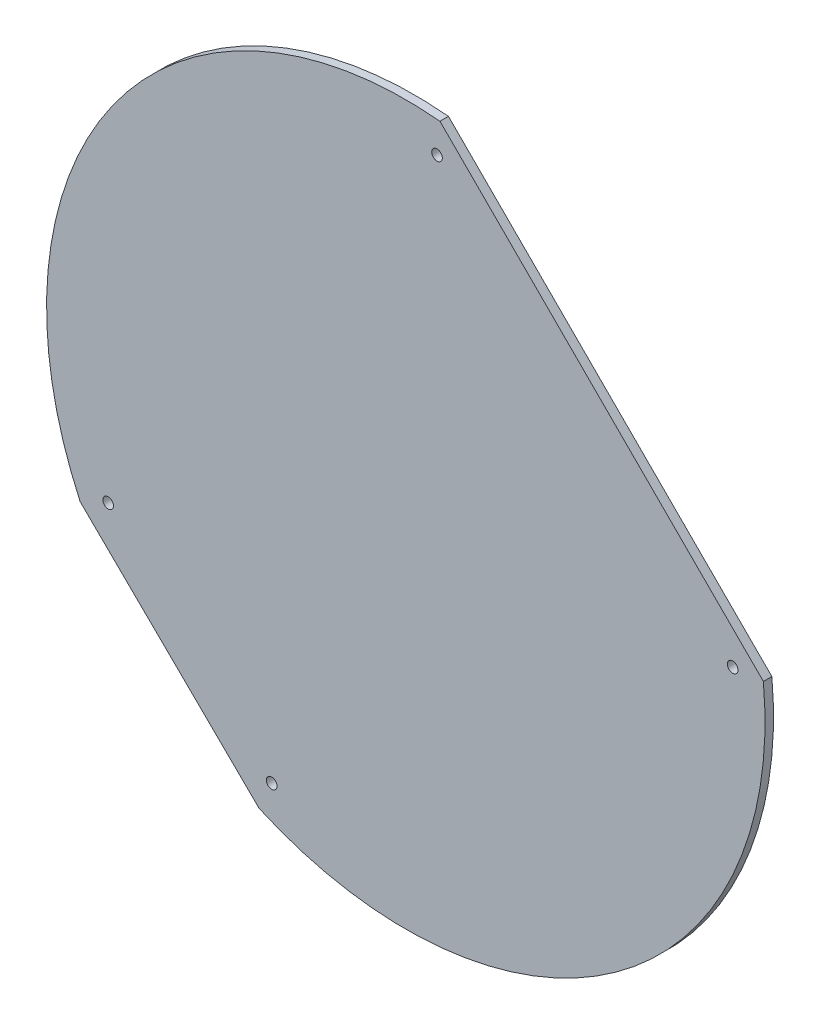
SolidWorks part; units mm, degrees
ref_plane "Plano frontal" through (0, 0, 0) normal (0, 0, 1) x (1, 0, 0)
ref_plane "Plano superior" through (0, 0, 0) normal (0, 1, 0) x (1, 0, 0)
ref_plane "Plano direito" through (0, 0, 0) normal (1, 0, 0) x (0, 0, -1)
sketch "Esboço1" plane through (0, 0, 0) normal (0, 0, 1) x (1, 0, 0)
  line L0 (0, 0) -> (0, 113.3267) construction
  line L1 (0, 113.3267) -> (0, -156.4068) construction
  line L2 (0, 0) -> (125.3449, 0) construction
  line L3 (125.3449, 0) -> (-126.5751, 0) construction
  line L4 (0, 56.6634) -> (84.1614, 64.705) construction
  line L5 (0, 56.6634) -> (-70.0412, 23.9979) construction
  line L6 (64.0195, 84.8468) -> (84.1614, 64.705)
  line L7 (28.4238, 120.4426) -> (64.0195, 84.8468)
  line L8 (8.0416, 140.8247) -> (28.4238, 120.4426)
  line L9 (-70.0412, 23.9979) -> (-31.5578, -13.8838) construction
  line L10 (0, 56.6634) -> (-34.5226, -20.5117) construction
  line L11 (0, 56.6634) -> (-70.0412, 23.9979) construction
  line L12 (-70.0412, 23.9979) -> (-76.6215, 20.929) construction
  line L13 (-31.5578, -13.8838) -> (0, 56.6634) construction
  line L14 (0, 56.6634) -> (-50.7995, 5.057) construction
  line L15 (0, 56.6634) -> (8.0416, 140.8247) construction
  line L16 (-76.6215, 20.929) -> (-34.5226, -20.5117)
  circle A0 centre (0, 56.6634) radius 77.2839 construction
  circle A1 centre (-31.5578, -13.8838) radius 1.25
  arc A2 (8.0416, 140.8247) -> (-76.6215, 20.929) centre (0, 56.6634) ccw
  circle A3 centre (0, 56.6634) radius 61.2839 construction
  arc A4 (-12.7802, -3.2731) -> (12.7802, -3.2731) centre (0, 56.6634) ccw construction
  arc A5 (-30.1405, 110.0231) -> (-15.214, -2.702) centre (0, 56.6634) ccw construction
  circle A6 centre (7.351, 133.5969) radius 1.25
  arc A8 (54.4624, 28.5642) -> (61.1931, 53.328) centre (0, 56.6634) ccw construction
  arc A10 (-3.0315, 117.8722) -> (-28.0777, 111.1368) centre (0, 56.6634) ccw construction
  arc A11 (61.2777, 55.7897) -> (-0.7105, 117.9431) centre (0, 56.6634) ccw construction
  circle A12 centre (76.9335, 64.0143) radius 1.25
  arc A13 (-34.5226, -20.5117) -> (84.1614, 64.705) centre (0, 56.6634) ccw
  arc A17 (15.214, -2.702) -> (53.2756, 26.3743) centre (0, 56.6634) ccw construction
  arc A18 (16.7578, 132.1086) -> (75.4452, 73.4211) centre (0, 56.6634) ccw construction
  circle A20 centre (-70.0412, 23.9979) radius 1.25
  point P62 (7.351, 133.5969)
  point P63 (76.9335, 64.0143)
  dimension "D2" = 2.5
  dimension "D3" = 2.5
  dimension "D15" = 2.5
  dimension "D16" = 2.5
  dimension "D14" = 27
  dimension "D13" = 16
extrude "Ressalto-extrusão1" add sketch "Esboço1" along normal blind 2
